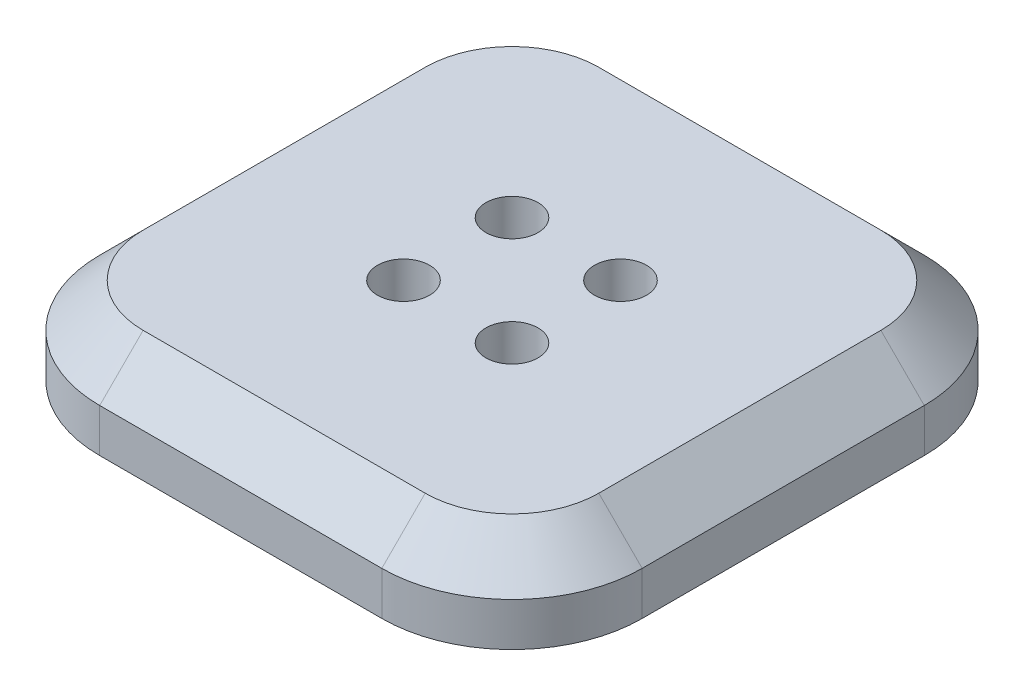
SolidWorks part; units mm, degrees
ref_plane "Alzado" through (0, 0, 0) normal (0, 0, 1) x (1, 0, 0)
ref_plane "Planta" through (0, 0, 0) normal (0, 1, 0) x (1, 0, 0)
ref_plane "Vista lateral" through (0, 0, 0) normal (1, 0, 0) x (0, 0, -1)
sketch "Croquis1" plane through (0, 0, 0) normal (0, 1, 0) x (1, 0, 0)
  line L1 (-62.5, -62.5) -> (62.5, -62.5)
  line L2 (-62.5, -62.5) -> (-62.5, 62.5)
  line L3 (-62.5, 62.5) -> (62.5, 62.5)
  line L4 (62.5, -62.5) -> (62.5, 62.5)
  line L5 (-62.5, -62.5) -> (62.5, 62.5) construction
  line L6 (-62.5, 62.5) -> (62.5, -62.5) construction
  point P0 (0, 0)
  dimension "D1" = 125
extrude "Saliente-Extruir1" add sketch "Croquis1" along normal blind 20
fillet "Redondeo1" radius 30 4 edges at (-62.5, 10, -62.5) (-62.5, 10, 62.5) (62.5, 10, -62.5) (62.5, 10, 62.5)
chamfer "Chaflán1" distance 10 angle 45 8 edges at (53.7132, 20, -53.7132) (0, 20, -62.5) (62.5, 20, 0) (-53.7132, 20, -53.7132) (53.7132, 20, 53.7132) (-62.5, 20, 0) (0, 20, 62.5) (-53.7132, 20, 53.7132)
sketch "Croquis2" plane through (0, 20, 0) normal (0, 1, 0) x (1, 0, 0)
  point P0 (0, 0)
sketch "Croquis3" plane through (0, 0, 0) normal (0, -1, 0) x (1, 0, 0)
  line L1 (-37.5, -37.5) -> (37.5, -37.5)
  line L2 (-37.5, -37.5) -> (-37.5, 37.5)
  line L3 (-37.5, 37.5) -> (37.5, 37.5)
  line L4 (37.5, -37.5) -> (37.5, 37.5)
  line L5 (-37.5, -37.5) -> (37.5, 37.5) construction
  line L6 (-37.5, 37.5) -> (37.5, -37.5) construction
  point P0 (0, 0)
  dimension "D1" = 75
hole_wizard "Taladro3" positions "Croquis8" profile "Croquis9" legacy
sketch "Croquis8" plane through (0, 0, 0) normal (0, -1, 0) x (-1, 0, 0)
  point P0 (-37.5, 37.5)
  point P3 (37.5, 37.5)
  point P6 (37.5, -37.5)
  point P9 (-37.5, -37.5)
sketch "Croquis9" plane through (37.5, 0, -37.5) normal (1, 0, 0) x (0, 0, -1)
  line L0 (0, 0) -> (0, 13.6052)
  line L1 (0, 13.6052) -> (6, 10)
  line L2 (6, 10) -> (6, 0)
  line L4 (6, 0) -> (0, 0)
  line L6 (0, 13.6052) -> (-6, 10) construction
  line L7 (0, -4.2442) -> (0, 117.3081) construction
  dimension "Diámetro" = 12
  dimension "Profundidad" = 10
  dimension "Ángulo de perforado" = 118
hole_wizard "Taladro4" positions "Croquis12" profile "Croquis13" legacy
sketch "Croquis12" plane through (0, 20, 0) normal (0, 1, 0) x (1, 0, 0)
  point P0 (0, 0)
sketch "Croquis13" plane through (0, 20, 0) normal (1, 0, 0) x (0, 0, 1)
  line L0 (0, 0) -> (0, 13.6052)
  line L1 (0, 13.6052) -> (6, 10)
  line L2 (6, 10) -> (6, 0)
  line L4 (6, 0) -> (0, 0)
  line L6 (0, 13.6052) -> (-6, 10) construction
  line L7 (0, -4.2442) -> (0, 117.3081) construction
  dimension "Diámetro" = 12
  dimension "Profundidad" = 10
  dimension "Ángulo de perforado" = 118
sketch "Croquis16" plane through (0, 20, 0) normal (0, 1, 0) x (1, 0, 0)
  line L1 (-12.5, -12.5) -> (12.5, -12.5)
  line L2 (-12.5, -12.5) -> (-12.5, 12.5)
  line L3 (-12.5, 12.5) -> (12.5, 12.5)
  line L4 (12.5, -12.5) -> (12.5, 12.5)
  line L5 (-12.5, -12.5) -> (12.5, 12.5) construction
  line L6 (-12.5, 12.5) -> (12.5, -12.5) construction
  point P0 (0, 0)
  dimension "D1" = 25
hole_wizard "Taladro5" positions "Croquis17" profile "Croquis18" legacy
sketch "Croquis17" plane through (0, 20, 0) normal (0, 1, 0) x (1, 0, 0)
  point P0 (-12.5, 12.5)
  point P3 (12.5, 12.5)
  point P6 (12.5, -12.5)
  point P9 (-12.5, -12.5)
sketch "Croquis18" plane through (-12.5, 20, -12.5) normal (1, 0, 0) x (0, 0, 1)
  line L0 (0, 0) -> (0, 13.6052)
  line L1 (0, 13.6052) -> (6, 10)
  line L2 (6, 10) -> (6, 0)
  line L4 (6, 0) -> (0, 0)
  line L6 (0, 13.6052) -> (-6, 10) construction
  line L7 (0, -4.2442) -> (0, 117.3081) construction
  dimension "Diámetro" = 12
  dimension "Profundidad" = 10
  dimension "Ángulo de perforado" = 118
hole_wizard "Taladro6" positions "Croquis21" profile "Croquis22" legacy
sketch "Croquis21" plane through (0, 20, 0) normal (0, 1, 0) x (1, 0, 0)
  point P0 (0, 0)
sketch "Croquis22" plane through (0, 20, 0) normal (1, 0, 0) x (0, 0, 1)
  line L0 (0, 0) -> (0, 13.6052)
  line L1 (0, 13.6052) -> (6, 10)
  line L2 (6, 10) -> (6, 0)
  line L4 (6, 0) -> (0, 0)
  line L6 (0, 13.6052) -> (-6, 10) construction
  line L7 (0, -4.2442) -> (0, 117.3081) construction
  dimension "Diámetro" = 12
  dimension "Profundidad" = 10
  dimension "Ángulo de perforado" = 118
equation "\"A\" = 125"
equation "\"B\" = 25"
equation "\"C\" = 75"
equation "\"D\"= 20"
equation "\"D1@Croquis1\" = \"A\""
equation "\"D1@Saliente-Extruir1\" = \"D\""
equation "\"D1@Croquis3\"=\"C\""
equation "\"D1@Croquis16\"=\"B\""
